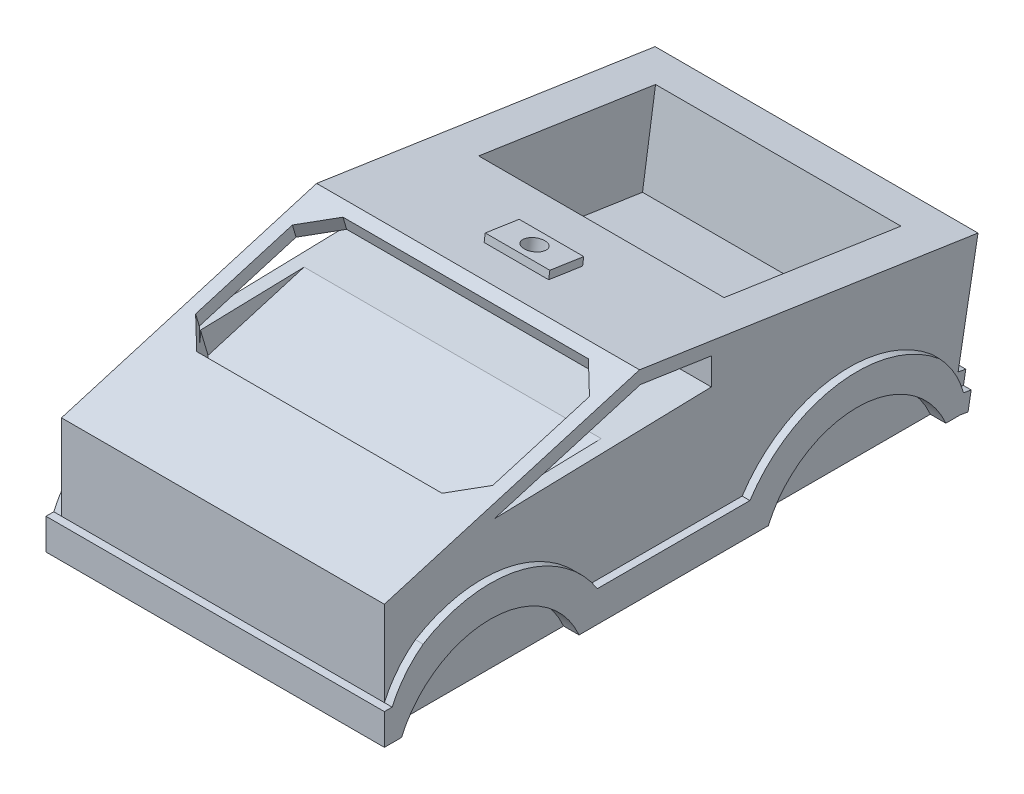
SolidWorks part; units mm, degrees
ref_plane "Front Plane" through (0, 0, 0) normal (0, 0, 1) x (1, 0, 0)
ref_plane "Top Plane" through (0, 0, 0) normal (0, 1, 0) x (1, 0, 0)
ref_plane "Right Plane" through (0, 0, 0) normal (1, 0, 0) x (0, 0, -1)
sketch "Sketch1" plane through (0, 0, 0) normal (1, 0, 0) x (0, 0, -1)
  line L0 (0, 0) -> (-220, 0)
  line L1 (-220, 0) -> (-220, 45)
  line L2 (-220, 45) -> (-121.2239, 74.2035)
  line L3 (-121.2239, 74.2035) -> (9.8106, 54.5513)
  line L4 (9.8106, 54.5513) -> (0, 0)
  line L5 (-177.4976, 52.352) -> (-120.8693, 69.0944)
  line L6 (-120.8693, 69.0944) -> (-93.4238, 64.9782)
  line L10 (-177.4976, 52.352) -> (-93.4238, 54.5513)
  line L11 (-93.4238, 54.5513) -> (-93.4238, 64.9782)
  line L12 (-215, 41.2643) -> (-120.8693, 69.0944) construction
  line L13 (-215, 5) -> (-215, 41.2643) construction
  line L14 (-4.181, 5) -> (-215, 5) construction
  line L15 (3.9784, 50.37) -> (-4.181, 5) construction
  line L16 (-120.8693, 69.0944) -> (3.9784, 50.37) construction
  dimension "D1" = 220
  dimension "D2" = 155
  dimension "D3" = 45
  dimension "D4" = 103.0027
  dimension "D5" = 132.5
  dimension "D6" = 5
extrude "Boss-Extrude1" add sketch "Sketch1" against normal blind 125
sketch "Sketch2" plane through (0, 101.1979, 29.9195) normal (0, 0.959, 0.2835) x (1, 0, 0)
  line L4 (-110, -159.28) -> (-15, -159.28)
  line L5 (-110, -100.2113) -> (-120, -110.2113)
  line L6 (-120, -149.28) -> (-110, -159.28)
  line L7 (-15, -159.28) -> (-5, -149.28)
  line L8 (-5, -193.214) -> (-5, -100.2113)
  line L9 (-5, -100.2113) -> (-120, -100.2113)
  line L10 (-120, -100.2113) -> (-120, -193.214)
  line L11 (-120, -193.214) -> (-5, -193.214)
  line L12 (-5, -149.28) -> (-5, -110.2113)
  line L13 (-15, -100.2113) -> (-110, -100.2113)
  line L14 (-120, -110.2113) -> (-120, -149.28)
  line L16 (-5, -110.2113) -> (-15, -100.2113)
  point P0 (-120, -159.28)
  point P1 (-5, -159.28)
  dimension "D1" = 5
extrude "Cut-Extrude1" cut sketch "Sketch2" against normal blind 17
sketch "Sketch3" plane through (0, 54.7902, -8.2173) normal (0, 0.9889, -0.1483) x (1, 0, 0)
  line L4 (-110, -82.6164) -> (-15, -82.6164)
  line L8 (-15, -115.8889) -> (-15, -13.3889)
  line L9 (-15, -13.3889) -> (-110, -13.3889)
  line L10 (-110, -13.3889) -> (-110, -115.8889)
  line L11 (-110, -115.8889) -> (-15, -115.8889)
  line L12 (-15, -82.6164) -> (-15, -13.3889)
  line L13 (-15, -13.3889) -> (-110, -13.3889)
  line L14 (-110, -13.3889) -> (-110, -82.6164)
  dimension "D1" = 15
extrude "Cut-Extrude2" cut sketch "Sketch3" against normal blind 34
sketch "Sketch4" plane through (0, 54.7902, -8.2173) normal (0, 0.9889, -0.1483) x (1, 0, 0)
  line L0 (-125, 1.6111) -> (-125, -130.8889) construction
  line L1 (-75, -102.6164) -> (-50, -102.6164)
  line L2 (-75, -102.6164) -> (-75, -115.8889)
  line L3 (-75, -115.8889) -> (-50, -115.8889)
  line L4 (-50, -102.6164) -> (-50, -115.8889)
  line L5 (0, 1.6111) -> (0, -130.8889) construction
  line L6 (-110, -82.6164) -> (-15, -82.6164) construction
  line L7 (-125, -130.8889) -> (0, -130.8889) construction
  dimension "D1" = 50
  dimension "D2" = 50
  dimension "D3" = 20
  dimension "D4" = 15
extrude "Boss-Extrude2" add sketch "Sketch4" along normal blind 3
sketch "Sketch5" plane through (0, 57.757, -8.6623) normal (0, 0.9889, -0.1483) x (1, 0, 0)
  line L0 (-75, -102.6164) -> (-50, -115.8889) construction
  line L1 (-50, -102.6164) -> (-75, -115.8889) construction
  circle A0 centre (-62.5, -109.2527) radius 4
  dimension "D1" = 8
extrude "Cut-Extrude3" cut sketch "Sketch5" against normal blind 26
sketch "Sketch6" plane through (0, 0, 0) normal (1, 0, 0) x (0, 0, -1)
  line L0 (-220, 45) -> (-220, 0) construction
  line L1 (-220, 0) -> (0, 0) construction
  circle A0 centre (-182, -15) radius 37.5
  circle A1 centre (-40, -15) radius 37.5
  dimension "D2" = 75
  dimension "D5" = 75
  dimension "D1" = 38
  dimension "D3" = 15
  dimension "D4" = 40
extrude "Cut-Extrude4" cut sketch "Sketch6" against normal blind 3
ref_plane "Plane1" through (-62.5, 0, 0) normal (1, 0, 0) x (0, 0, -1)
mirror "Mirror1" about plane through (-62.5, 0, 0) normal (1, 0, 0) of "Cut-Extrude4"
sketch "Sketch7" plane through (0, 0, 220) normal (0, 0, 1) x (1, 0, 0)
  line L4 (-113, 12) -> (-125, 12)
  line L5 (-125, 45) -> (-125, 0) construction
  line L6 (-12, 12) -> (0, 12)
  line L7 (0, 45) -> (0, 0) construction
  line L8 (-12, 12) -> (-12, 33)
  line L9 (-12, 33) -> (-113, 33)
  line L10 (-113, 33) -> (-113, 12)
  line L11 (-113, 12) -> (-12, 12)
  line L15 (-113, 12) -> (-12, 12)
  line L16 (-125, 12) -> (-125, 0)
  line L17 (-125, 0) -> (0, 0)
  line L18 (0, 0) -> (0, 12)
  dimension "D1" = 12
extrude "Boss-Extrude3" add sketch "Sketch7" along normal blind 3
sketch "Sketch8" plane through (0, 0, 0) normal (1, 0, 0) x (0, 0, -1)
  line L9 (0, 0) -> (9.8106, 54.5513) construction
  line L18 (-140.512, 12) -> (-81.488, 12)
  line L19 (-8.0853, 22.8378) -> (-4.1866, 44.5163)
  line L20 (-4.1866, 44.5163) -> (-120.3728, 61.9416)
  line L21 (-120.3728, 61.9416) -> (-208, 36.0344)
  line L22 (-208, 36.0344) -> (-208, 27.1218)
  line L23 (-140.512, 12) -> (-81.488, 12)
  line L24 (-8.0853, 22.8378) -> (-4.1866, 44.5163)
  line L25 (-4.1866, 44.5163) -> (-120.3728, 61.9416)
  line L26 (-120.3728, 61.9416) -> (-208, 36.0344)
  line L27 (-208, 36.0344) -> (-208, 27.1218)
  line L62 (-147.6307, 0) -> (-74.3693, 0)
  line L63 (-5.6307, 0) -> (0, 0)
  line L64 (0, 0) -> (1.2211, 6.7897)
  line L65 (-216.3693, 0) -> (-223, 0)
  line L66 (-223, 0) -> (-223, 12)
  line L67 (-223, 12) -> (-220, 12)
  arc A2 (-208, 27.1218) -> (-220, 12) centre (-185.2099, -3.2856) ccw
  arc A3 (-8.0853, 22.8378) -> (1.2211, 6.7897) centre (-35.3103, -3.6725) cw
  arc A4 (-140.512, 12) -> (-208, 27.1218) centre (-182, -15) ccw
  arc A5 (-8.0853, 22.8378) -> (-81.488, 12) centre (-40, -15) ccw
  arc A6 (-140.512, 12) -> (-208, 27.1218) centre (-182, -15) ccw
  arc A7 (-8.0853, 22.8378) -> (-81.488, 12) centre (-40, -15) ccw
  arc A10 (-147.6307, 0) -> (-216.3693, 0) centre (-182, -15) ccw
  arc A11 (-147.6307, 0) -> (-216.3693, 0) centre (-182, -15) ccw
  arc A21 (-74.3693, 0) -> (-5.6307, 0) centre (-40, -15) cw
  arc M9 (-216.3693, 0) -> (-147.6307, 0) centre (-182, -15) cw
  line M10 (-147.6307, 0) -> (-74.3693, 0)
  arc M11 (-74.3693, 0) -> (-5.6307, 0) centre (-40, -15) cw
  line M12 (-5.6307, 0) -> (0, 0)
  line M13 (0, 0) -> (9.8106, 54.5513)
  line M17 (-220, 12) -> (-223, 12)
  line M18 (-223, 12) -> (-223, 0)
  line M19 (-223, 0) -> (-216.3693, 0)
  dimension "D2" = 38
  dimension "D3" = 38
  dimension "D1" = 12
  dimension "D4" = 0
extrude "Boss-Extrude4" add sketch "Sketch8" along normal blind 3 contours A3 A7 L23 A6 A2 M17 M18 M19 M9 M10 M11 M12 M13
mirror "Mirror2" about plane through (-62.5, 0, 0) normal (1, 0, 0) of "Boss-Extrude4"
sketch "Sketch9" plane through (0, 0, 0) normal (0, -0.177, -0.9842) x (-1, 0, 0)
  line L8 (12, 12) -> (0, 12)
  line L9 (0, 6.8987) -> (0, 55.4264) construction
  line L10 (113, 12) -> (125, 12)
  line L11 (125, 6.8987) -> (125, 21.0461) construction
  line L12 (0, 12) -> (0, 6.8987)
  line L13 (0, 6.8987) -> (-3, 6.8987)
  line L14 (-3, 6.8987) -> (-3, 0)
  line L15 (-3, 0) -> (128, 0)
  line L16 (12, 43.4264) -> (12, 12)
  line L17 (12, 12) -> (113, 12)
  line L18 (113, 12) -> (113, 43.4264)
  line L19 (113, 43.4264) -> (12, 43.4264)
  line L21 (12, 12) -> (113, 12)
  line L24 (128, 0) -> (128, 6.8987)
  line L25 (128, 6.8987) -> (125, 6.8987)
  line L26 (125, 6.8987) -> (125, 12)
  dimension "D1" = 12
extrude "Boss-Extrude5" add sketch "Sketch9" along normal blind 3
